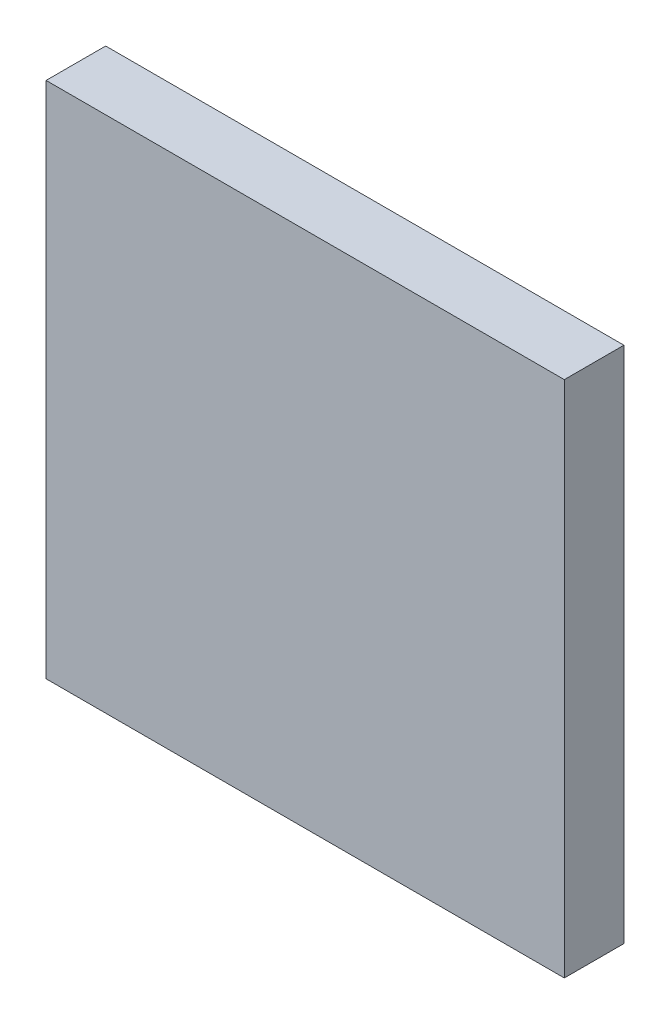
SolidWorks part; units mm, degrees
material "ABS PC"
ref_plane "Front Plane" through (0, 0, 0) normal (0, 0, 1) x (1, 0, 0)
ref_plane "Top Plane" through (0, 0, 0) normal (0, 1, 0) x (1, 0, 0)
ref_plane "Right Plane" through (0, 0, 0) normal (1, 0, 0) x (0, 0, -1)
sketch "Sketch1" plane through (0, 0, 0) normal (0, 0, 1) x (1, 0, 0)
  line L1 (0, 0) -> (25.4, 0)
  line L2 (0, 0) -> (0, 25.4)
  line L3 (0, 25.4) -> (25.4, 25.4)
  line L4 (25.4, 0) -> (25.4, 25.4)
  dimension "D1" = 25.4
  dimension "D2" = 25.4
extrude "Boss-Extrude1" add sketch "Sketch1" against normal blind 2.921
